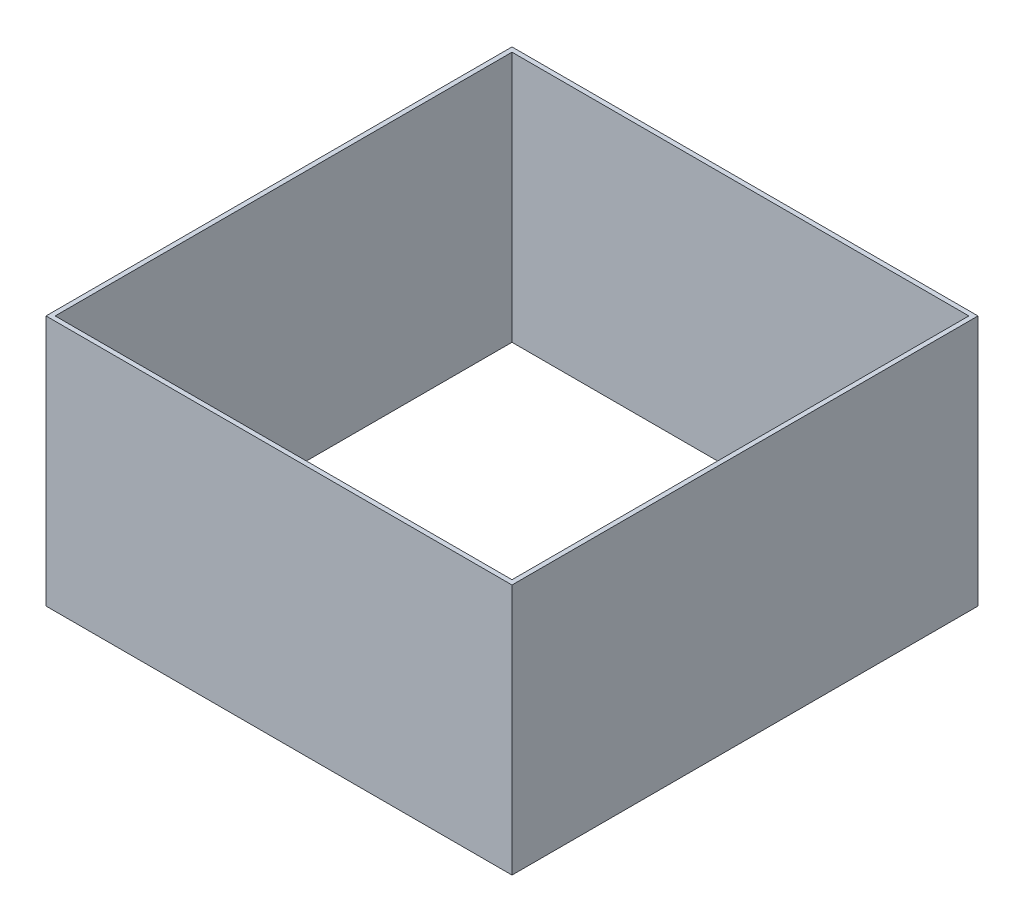
SolidWorks part; units mm, degrees
ref_plane "Front Plane" through (0, 0, 0) normal (0, 0, 1) x (1, 0, 0)
ref_plane "Top Plane" through (0, 0, 0) normal (0, 1, 0) x (1, 0, 0)
ref_plane "Right Plane" through (0, 0, 0) normal (1, 0, 0) x (0, 0, -1)
sketch "Sketch1" plane through (0, 0, 0) normal (0, 1, 0) x (1, 0, 0)
  line L0 (1, 1) -> (101, 1)
  line L1 (0, 0) -> (102, 0)
  line L2 (0, 0) -> (0, 102)
  line L3 (0, 102) -> (102, 102)
  line L4 (102, 0) -> (102, 102)
  line L9 (101, 1) -> (101, 101)
  line L10 (1, 101) -> (101, 101)
  line L11 (1, 1) -> (1, 101)
  dimension "D1" = 102
  dimension "D2" = 102
  dimension "D3" = 1
extrude "Boss-Extrude1" add sketch "Sketch1" along normal blind 55
